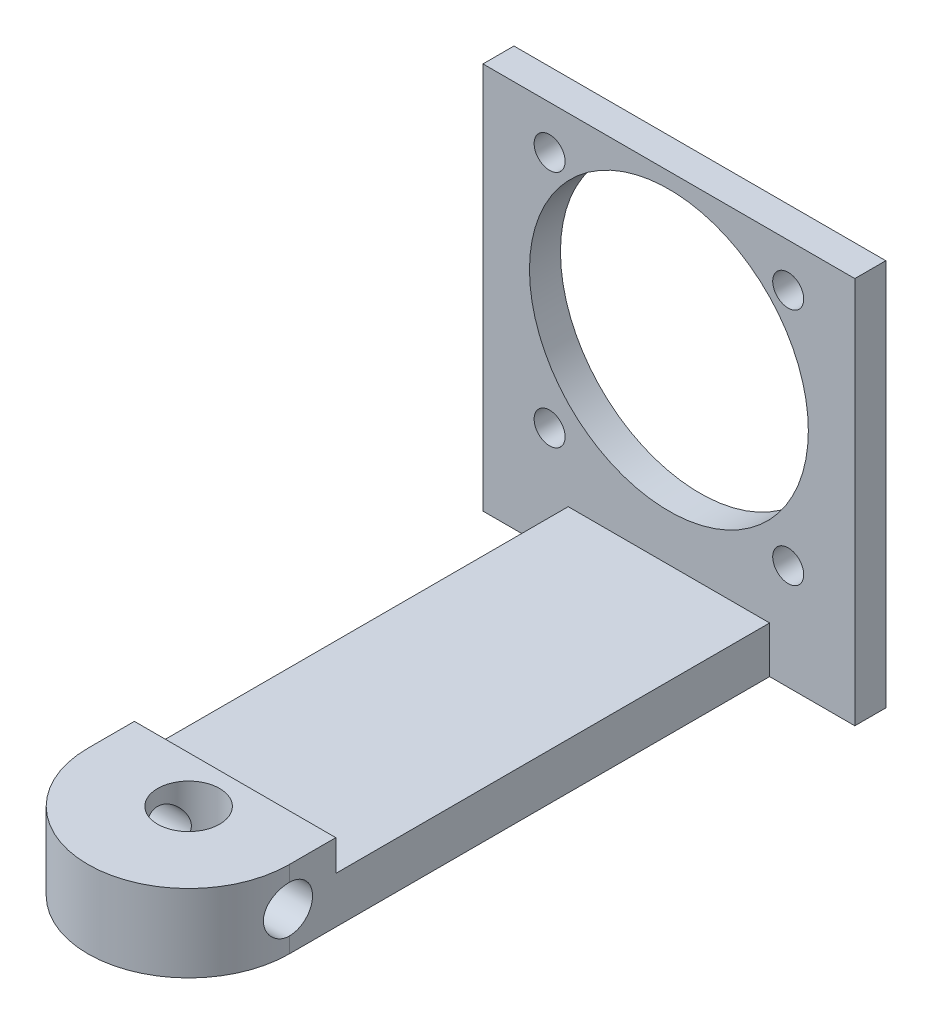
SolidWorks part; units mm, degrees
material "3.0205 (EN-AW 1200)"
ref_plane "前视基准面" through (0, 0, 0) normal (0, 0, 1) x (1, 0, 0)
ref_plane "上视基准面" through (0, 0, 0) normal (0, 1, 0) x (1, 0, 0)
ref_plane "右视基准面" through (0, 0, 0) normal (1, 0, 0) x (0, 0, -1)
sketch "草图1" plane through (0, 0, 0) normal (0, 1, 0) x (1, 0, 0)
  line L1 (5, 0) -> (2.5, 4.3301)
  line L2 (2.5, 4.3301) -> (-2.5, 4.3301)
  line L3 (-2.5, 4.3301) -> (-5, 0)
  line L4 (-5, 0) -> (-2.5, -4.3301)
  line L5 (-2.5, -4.3301) -> (2.5, -4.3301)
  line L6 (5, 0) -> (2.5, -4.3301)
sketch "草图2" plane through (0, 0, 0) normal (0, 1, 0) x (1, 0, 0)
  circle A0 centre (0, 0) radius 6.5
extrude "凸台-拉伸1" add sketch "草图2" along normal blind 5
sketch "草图3" plane through (0, 5, 0) normal (0, 1, 0) x (1, 0, 0)
  circle A0 centre (0, 0) radius 2
extrude "切除-拉伸2" cut sketch "草图3" against normal through all
sketch "草图4" plane through (0, 5, 0) normal (0, 1, 0) x (1, 0, 0)
  line L1 (6.5, 31) -> (3.8991, 31)
  line L3 (-6.5, 0) -> (-6.5, 31)
  line L4 (-6.5, 31) -> (-4.1009, 31)
  line L7 (-6.5, 0) -> (6.5, 0)
  line L8 (6.5, 0) -> (6.5, 31)
  line L11 (-4.1009, 31) -> (3.8991, 31)
  circle A0 centre (0, 0) radius 6.5 construction
  circle A1 centre (0, 0) radius 6.5
extrude "凸台-拉伸2" add sketch "草图4" against normal blind 5
sketch "草图6" plane through (0, 0, -31) normal (0, 0, -1) x (-1, 0, 0)
  line L5 (-15.5564, 5.1908) -> (-3.328, -1.1893)
sketch "草图18" plane through (0, 0, 0) normal (0, -1, 0) x (1, 0, 0)
  circle A0 centre (0, 0) radius 2.5328
sketch "草图20" plane through (0, 0, 0) normal (1, 0, 0) x (0, 0, -1)
  line L0 (0, 5) -> (0, 3)
  circle A0 centre (0, 3) radius 1.5
sketch "草图21" plane through (0, 0, -31) normal (0, 0, -1) x (-1, 0, 0)
  line L0 (0, 0) -> (12, 0)
  line L1 (12, 0) -> (12, 25)
  line L2 (12, 25) -> (-12, 25)
  line L3 (-12, 25) -> (-12, 0)
  line L4 (-12, 0) -> (0, 0)
extrude "凸台-拉伸3" add sketch "草图21" along normal blind 2
sketch "草图22" plane through (0, 0, -31) normal (0, 0, 1) x (1, 0, 0)
  line L0 (-6.5, 5) -> (-12, 5)
  line L1 (-12, 0) -> (-12, 25) construction
  line L2 (0, 5) -> (0, 25)
  line L3 (-6.5, 5) -> (6.5, 5) construction
  line L4 (-12, 25) -> (12, 25) construction
  line L5 (0, 15) -> (7.7, 15)
  line L6 (7.7, 15) -> (7.7, 22.2)
  line L7 (7.7, 22.2) -> (-7.7, 22.2)
  line L8 (-7.7, 22.2) -> (-7.7, 6.8)
  line L9 (-7.7, 6.8) -> (7.7, 6.8)
  circle A0 centre (0, 15) radius 9
  circle A1 centre (7.7, 22.2) radius 1
  circle A2 centre (-7.7, 22.2) radius 1
  circle A3 centre (-7.7, 6.8) radius 1
  circle A4 centre (7.7, 6.8) radius 1
extrude "切除-拉伸4" cut sketch "草图22" against normal blind 2 contours A0 | A3 | A4 | A1 | A2
sketch "草图23" plane through (0, 0, 0) normal (1, 0, 0) x (0, 0, -1)
  line L0 (-6.5, 2.5) -> (0, 2.5)
  line L1 (-6.5, 5) -> (-6.5, 0) construction
  circle A0 centre (0, 2.5) radius 1.5
extrude "切除-拉伸6" cut sketch "草图23" against normal through all both and the other way through all contours A0
sketch "草图24" plane through (0, 5, 0) normal (0, 1, 0) x (1, 0, 0)
  line L0 (6.5, 0) -> (6.5, 31) construction
  line L1 (-6.5, 31) -> (6.5, 31)
  line L2 (-6.5, 31) -> (-6.5, 3)
  line L3 (-6.5, 3) -> (6.5, 3)
  line L4 (6.5, 31) -> (6.5, 3)
extrude "切除-拉伸7" cut sketch "草图24" against normal blind 2
